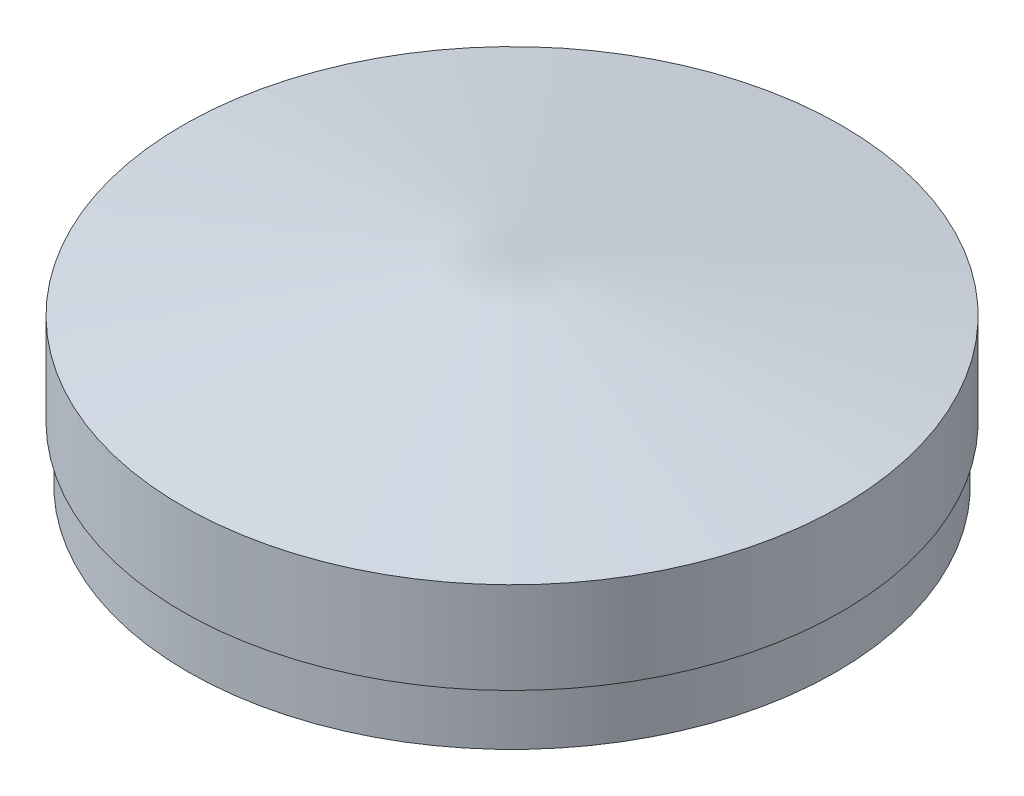
SolidWorks part; units mm, degrees
material "Nickel"
ref_plane "Front Plane" through (0, 0, 0) normal (0, 0, 1) x (1, 0, 0)
ref_plane "Top Plane" through (0, 0, 0) normal (0, 1, 0) x (1, 0, 0)
ref_plane "Right Plane" through (0, 0, 0) normal (1, 0, 0) x (0, 0, -1)
sketch "Sketch1" plane through (0, 0, 0) normal (1, 0, 0) x (0, 0, -1)
  line L0 (0, 0) -> (0, 3)
  line L1 (0, 3) -> (18, 0)
  line L2 (18, 0) -> (0, 0)
  point P3 (0, 0)
  dimension "D1" = 3
  dimension "D2" = 18
revolve "Revolve1" add sketch "Sketch1" angle 360 about L0
sketch "Sketch2" plane through (0, 0, 0) normal (0, -1, 0) x (1, 0, 0)
  circle A0 centre (0, 0) radius 18
  circle A1 centre (0, 0) radius 18 construction
extrude "Boss-Extrude1" add sketch "Sketch2" along normal blind 5
sketch "Sketch3" plane through (0, -5, 0) normal (0, -1, 0) x (1, 0, 0)
  circle A0 centre (0, 0) radius 17.7
  circle A1 centre (0, 0) radius 16.7
  point P5 (0, 0)
  dimension "D1" = 35.4
  dimension "D2" = 1
extrude "Boss-Extrude2" add sketch "Sketch3" along normal blind 3
sketch "Sketch4" plane through (0, -5, 0) normal (0, -1, 0) x (1, 0, 0)
  circle A0 centre (0, 0) radius 16.7
  circle A1 centre (0, 0) radius 16.7 construction
extrude "Cut-Extrude1" cut sketch "Sketch4" along a picked direction on the side against the normal blind 5
sketch "Sketch5" plane through (0, 0, 0) normal (0, -1, 0) x (1, 0, 0)
  circle A0 centre (0, 0) radius 2.5
  circle A1 centre (0, 0) radius 2
  dimension "D1" = 5
  dimension "D2" = 4
extrude "Boss-Extrude3" add sketch "Sketch5" along normal blind 8
